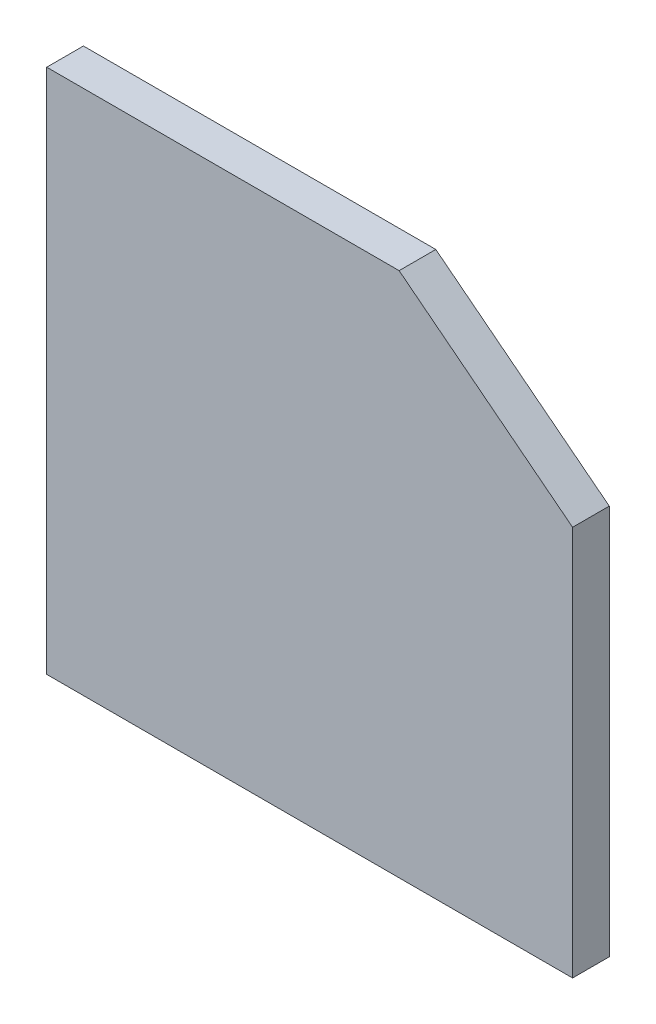
SolidWorks part; units mm, degrees
ref_plane "Front Plane" through (0, 0, 0) normal (0, 0, 1) x (1, 0, 0)
ref_plane "Top Plane" through (0, 0, 0) normal (0, 1, 0) x (1, 0, 0)
ref_plane "Right Plane" through (0, 0, 0) normal (1, 0, 0) x (0, 0, -1)
sketch "Sketch1" plane through (0, 0, 0) normal (0, 0, 1) x (1, 0, 0)
  line L0 (28.8158, 43) -> (43, 31.9181)
  line L1 (0, 0) -> (43, 0)
  line L2 (0, 0) -> (0, 43)
  line L3 (0, 43) -> (43, 43)
  line L4 (43, 0) -> (43, 43)
  dimension "D1" = 43
  dimension "D2" = 43
  dimension "D3" = 38
  dimension "D4" = 18
extrude "Boss-Extrude1" add sketch "Sketch1" along normal blind 3 contours L1 L4 L0 L3 L2
